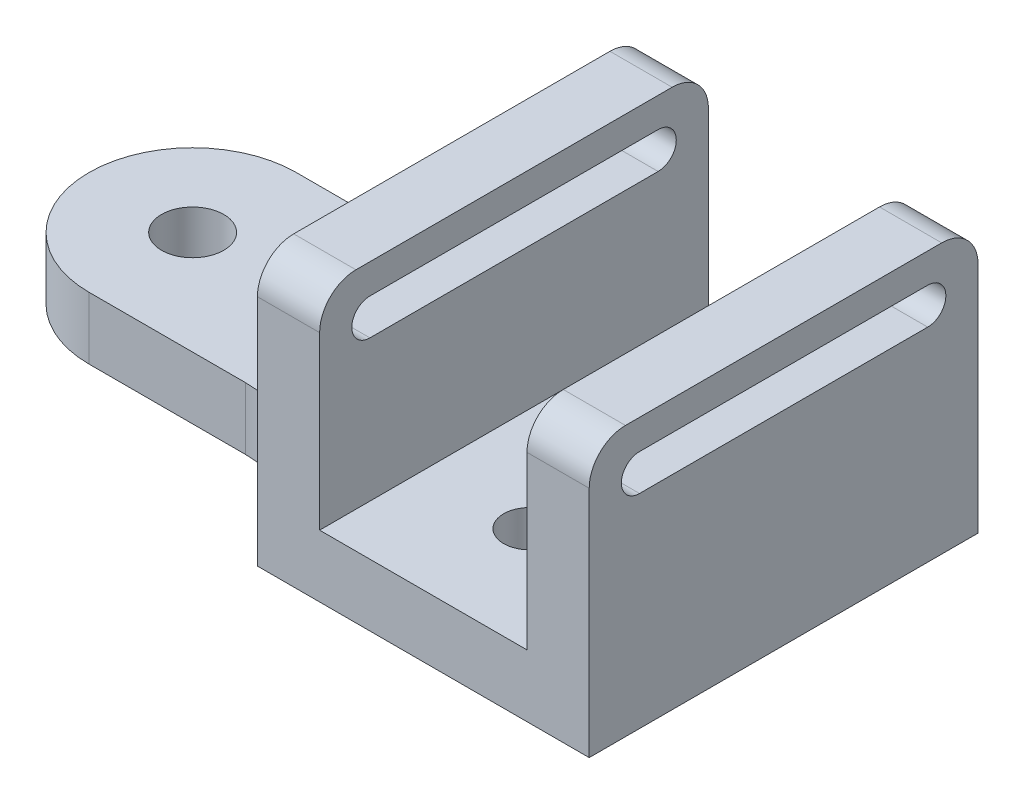
SolidWorks part; units mm, degrees
ref_plane "前视基准面" through (0, 0, 0) normal (0, 0, 1) x (1, 0, 0)
ref_plane "上视基准面" through (0, 0, 0) normal (0, 1, 0) x (1, 0, 0)
ref_plane "右视基准面" through (0, 0, 0) normal (1, 0, 0) x (0, 0, -1)
other "Configuration Table"
sketch "草图1" plane through (0, 0, 0) normal (0, 1, 0) x (1, 0, 0)
  line L0 (-910.9232, 431.9449) -> (-144.9388, 431.9449)
  line L1 (359.0768, 876.4449) -> (1984.6768, 876.4449)
  line L2 (359.0768, 876.4449) -> (359.0768, -1028.5551)
  line L3 (359.0768, -1028.5551) -> (1984.6768, -1028.5551)
  line L4 (1984.6768, 876.4449) -> (1984.6768, -1028.5551)
  line L5 (-910.9232, -584.0551) -> (-144.9388, -584.0551)
  line L6 (-144.9388, 431.9449) -> (-910.9232, 431.9449)
  line L7 (-144.9388, 431.9449) -> (-148.9232, 431.9449)
  arc A0 (-910.9232, 431.9449) -> (-910.9232, -584.0551) centre (-910.9232, -76.0551) ccw
  circle A1 centre (-910.9232, -76.0551) radius 152.4
  circle A2 centre (1171.8768, -507.8551) radius 127
  circle A3 centre (1160.2617, 355.7449) radius 127
  arc A7 (-144.9388, 431.9449) -> (359.0768, 876.4449) centre (-144.9388, 939.9449) ccw
  arc A8 (-144.9388, -584.0551) -> (359.0768, -1028.5551) centre (-144.9388, -1092.0551) cw
  point P9 (0, 0)
  point P12 (0, 0)
extrude "凸台-拉伸3" add sketch "草图1" along normal blind 304.8 contours L5 A8 L2 A7 L6 L0 A0 A1 | L4 L1 L2 L3 A3 A2
sketch "草图11" plane through (0, 0, 0) normal (0, 0, 1) x (1, 0, 0)
sketch "草图30" plane through (1984.6768, 0, 0) normal (1, 0, 0) x (0, 0, -1)
  line L0 (-782.1196, 1175.3989) -> (630.0093, 1175.3989)
  line L1 (-1028.5551, 304.8) -> (876.4449, 304.8)
  line L2 (-1028.5551, 304.8) -> (-1028.5551, 1143)
  line L3 (-850.7551, 1320.8) -> (698.6449, 1320.8)
  line L4 (876.4449, 304.8) -> (876.4449, 1143)
  line L5 (-782.1196, 997.5989) -> (630.0093, 997.5989)
  arc A0 (-850.7551, 1320.8) -> (-1028.5551, 1143) centre (-850.7551, 1143) ccw
  arc A1 (876.4449, 1143) -> (698.6449, 1320.8) centre (698.6449, 1143) ccw
  arc A2 (-782.1196, 1175.3989) -> (-782.1196, 997.5989) centre (-782.1196, 1086.4989) ccw
  arc A3 (630.0093, 997.5989) -> (630.0093, 1175.3989) centre (630.0093, 1086.4989) ccw
  dimension "D2" = 177.8
  dimension "D1" = 1016
  dimension "D4" = 1905
extrude "凸台-拉伸5" add sketch "草图30" against normal blind 304.8 contours A1 L3 A0 L2 L1 L4 | A3 L0 A2 L5
ref_plane "基准面8" through (1171.8768, 0, 0) normal (-1, 0, 0) x (0, 0, 1)
mirror "镜向2" about plane through (1171.8768, 0, 0) normal (-1, 0, 0) of "凸台-拉伸5"
